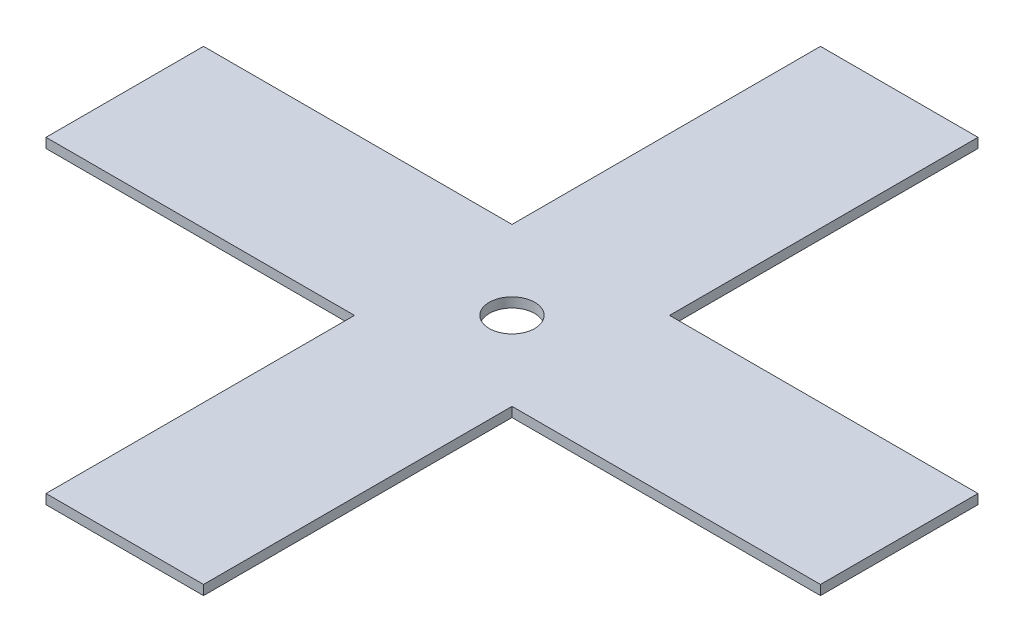
SolidWorks part; units mm, degrees
ref_plane "Front Plane" through (0, 0, 0) normal (0, 0, 1) x (1, 0, 0)
ref_plane "Top Plane" through (0, 0, 0) normal (0, 1, 0) x (1, 0, 0)
ref_plane "Right Plane" through (0, 0, 0) normal (1, 0, 0) x (0, 0, -1)
sketch "Sketch1" plane through (0, 0, 0) normal (0, 1, 0) x (1, 0, 0)
  line L0 (0, 0) -> (0, 37.3)
  line L1 (0, 37.3) -> (-37.3, 37.3)
  line L2 (-37.3, 37.3) -> (-37.3, 56.35)
  line L3 (-37.3, 56.35) -> (0, 56.35)
  line L4 (0, 56.35) -> (0, 93.65)
  line L5 (0, 93.65) -> (19.05, 93.65)
  line L6 (19.05, 93.65) -> (19.05, 56.35)
  line L7 (19.05, 56.35) -> (56.35, 56.35)
  line L8 (56.35, 56.35) -> (56.35, 37.3)
  line L9 (56.35, 37.3) -> (19.05, 37.3)
  line L10 (19.05, 37.3) -> (19.05, 0)
  line L11 (19.05, 0) -> (0, 0)
  line L12 (0, 56.35) -> (19.05, 37.3) construction
  line L13 (0, 37.3) -> (19.05, 56.35) construction
  circle A0 centre (9.525, 46.825) radius 2.75
  dimension "D3" = 5.5
  dimension "D1" = 93.65
  dimension "D2" = 19.05
extrude "Boss-Extrude1" add sketch "Sketch1" along normal blind 1.175
